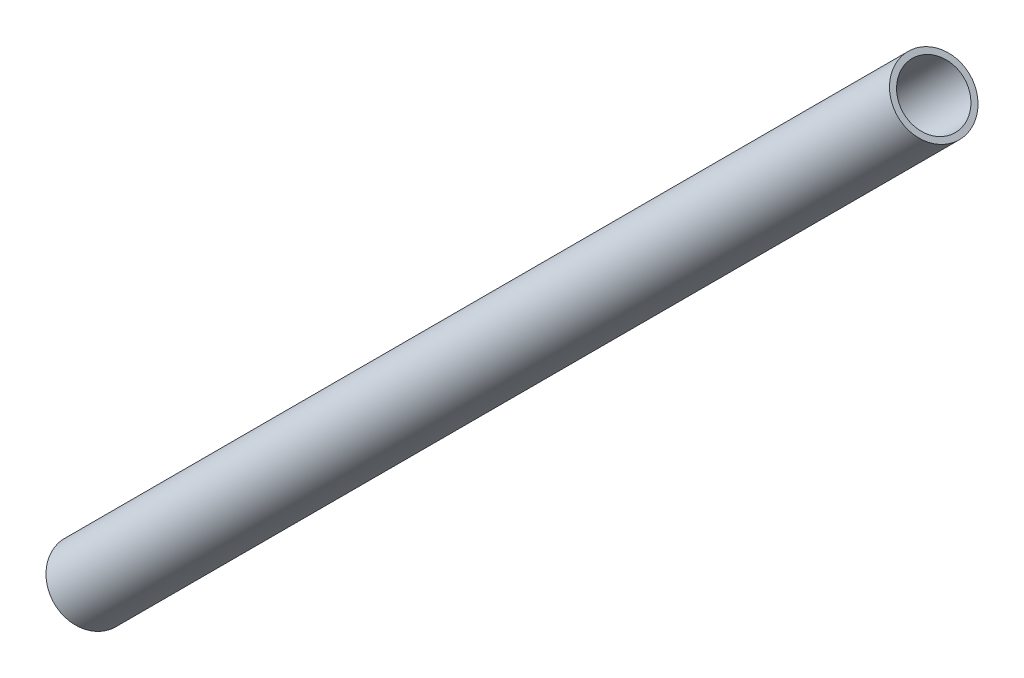
SolidWorks part; units mm, degrees
ref_plane "Front Plane" through (0, 0, 0) normal (0, 0, 1) x (1, 0, 0)
ref_plane "Top Plane" through (0, 0, 0) normal (0, 1, 0) x (1, 0, 0)
ref_plane "Right Plane" through (0, 0, 0) normal (1, 0, 0) x (0, 0, -1)
sketch "Sketch2" plane through (94.8593, 94.8593, 0) normal (-0.7071, -0.7071, 0) x (0, 0, 1)
  circle A0 centre (-10, -38.4567) radius 4.2
  circle A1 centre (-10, -38.4567) radius 5
  circle A2 centre (-10, -38.4567) radius 5
  dimension "D1" = 0
extrude "Boss-Extrude1" add sketch "Sketch2" along normal blind 165
